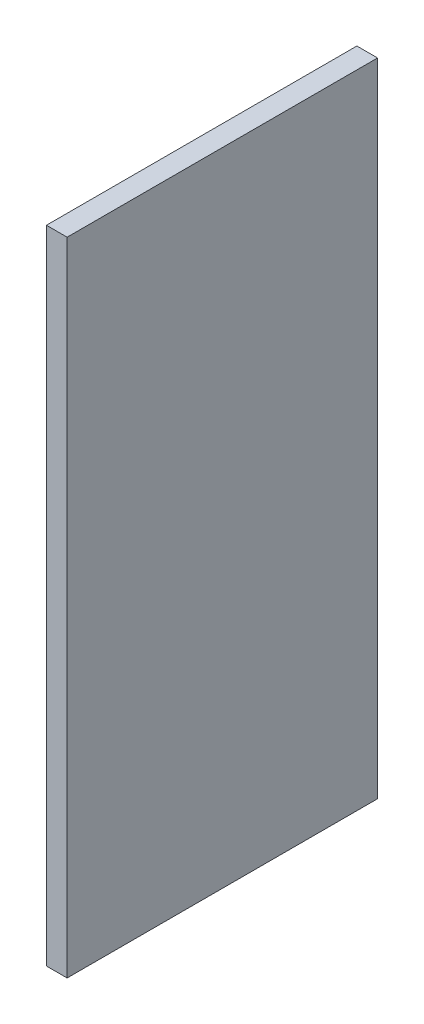
SolidWorks part; units mm, degrees
ref_plane "Front Plane" through (0, 0, 0) normal (0, 0, 1) x (1, 0, 0)
ref_plane "Top Plane" through (0, 0, 0) normal (0, 1, 0) x (1, 0, 0)
ref_plane "Right Plane" through (0, 0, 0) normal (1, 0, 0) x (0, 0, -1)
sketch "Sketch1" plane through (0, 0, 0) normal (0, 1, 0) x (1, 0, 0)
  line L1 (0, 0) -> (12.7, 0)
  line L2 (0, 0) -> (0, 190.5)
  line L3 (0, 190.5) -> (12.7, 190.5)
  line L4 (12.7, 0) -> (12.7, 190.5)
  dimension "D1" = 12.7
  dimension "D2" = 190.5
extrude "Boss-Extrude1" add sketch "Sketch1" along normal blind 393.7
